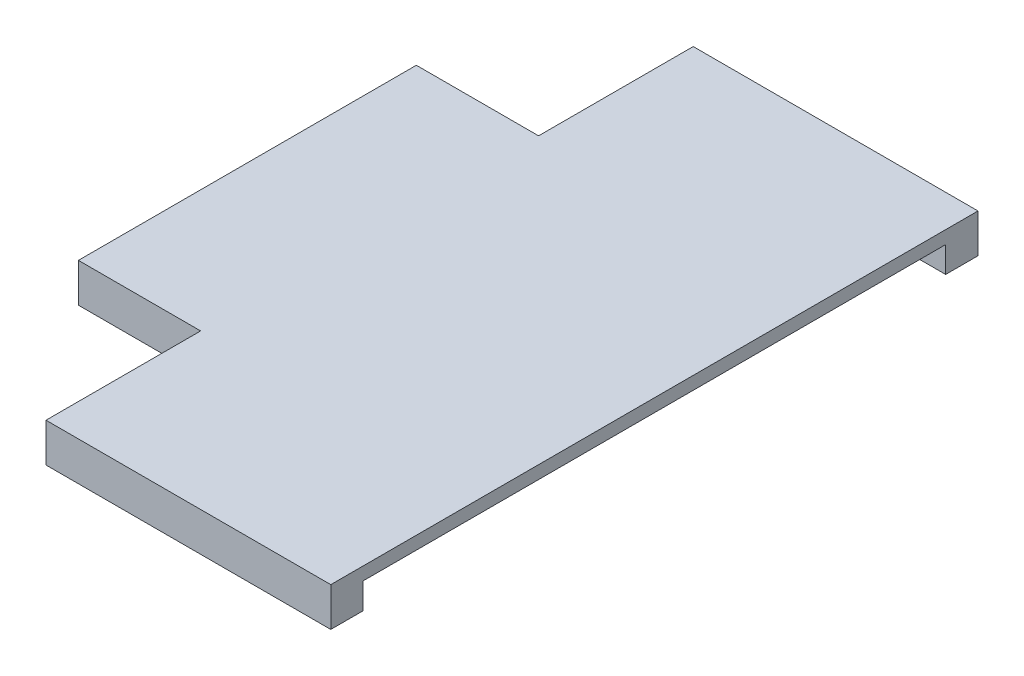
SolidWorks part; units mm, degrees
ref_plane "Спереди" through (0, 0, 0) normal (0, 0, 1) x (1, 0, 0)
ref_plane "Сверху" through (0, 0, 0) normal (0, 1, 0) x (1, 0, 0)
ref_plane "Справа" through (0, 0, 0) normal (1, 0, 0) x (0, 0, -1)
sketch "Эскиз1" plane through (0, 0, 0) normal (0, 1, 0) x (1, 0, 0)
  line L1 (-12, 0) -> (-56, 0)
  line L3 (-12, 100) -> (-56, 100)
  line L4 (-74.8865, 23.8937) -> (-74.8865, 76.1063)
  line L6 (-12, 100) -> (-12, 0)
  line L9 (-74.8865, 76.1063) -> (-56, 76.1063)
  line L10 (-56, 100) -> (-56, 76.1063)
  line L11 (-74.8865, 50) -> (-102.9844, 50) construction
  line L12 (-74.8865, 23.8937) -> (-56, 23.8937)
  line L13 (-56, 0) -> (-56, 23.8937)
extrude "Вытянуть1" add sketch "Эскиз1" along normal blind 6
sketch "Эскиз2" plane through (0, 0, 0) normal (0, -1, 0) x (1, 0, 0)
  line L0 (-56, -5) -> (-12, -5)
  line L1 (-56, -23.8937) -> (-56, 0) construction
  line L2 (-12, 0) -> (-12, -100) construction
  line L3 (-56, 0) -> (-12, 0) construction
  line L4 (-12, -50) -> (58.6789, -50) construction
  line L5 (-56, -95) -> (-12, -95)
  line L6 (-56, -5) -> (-56, -26.7167)
  line L7 (-74.8865, -26.7167) -> (-56, -26.7167)
  line L8 (-74.8865, -76.1063) -> (-74.8865, -23.8937) construction
  line L9 (-56, -95) -> (-56, -73.2833)
  line L10 (-74.8865, -73.2833) -> (-56, -73.2833)
  line L11 (-74.8865, -73.2833) -> (-74.8865, -26.7167)
  line L12 (-12, -5) -> (-12, -95)
  dimension "D1" = 5
extrude "Вытянуть2" cut sketch "Эскиз2" against normal blind 4
